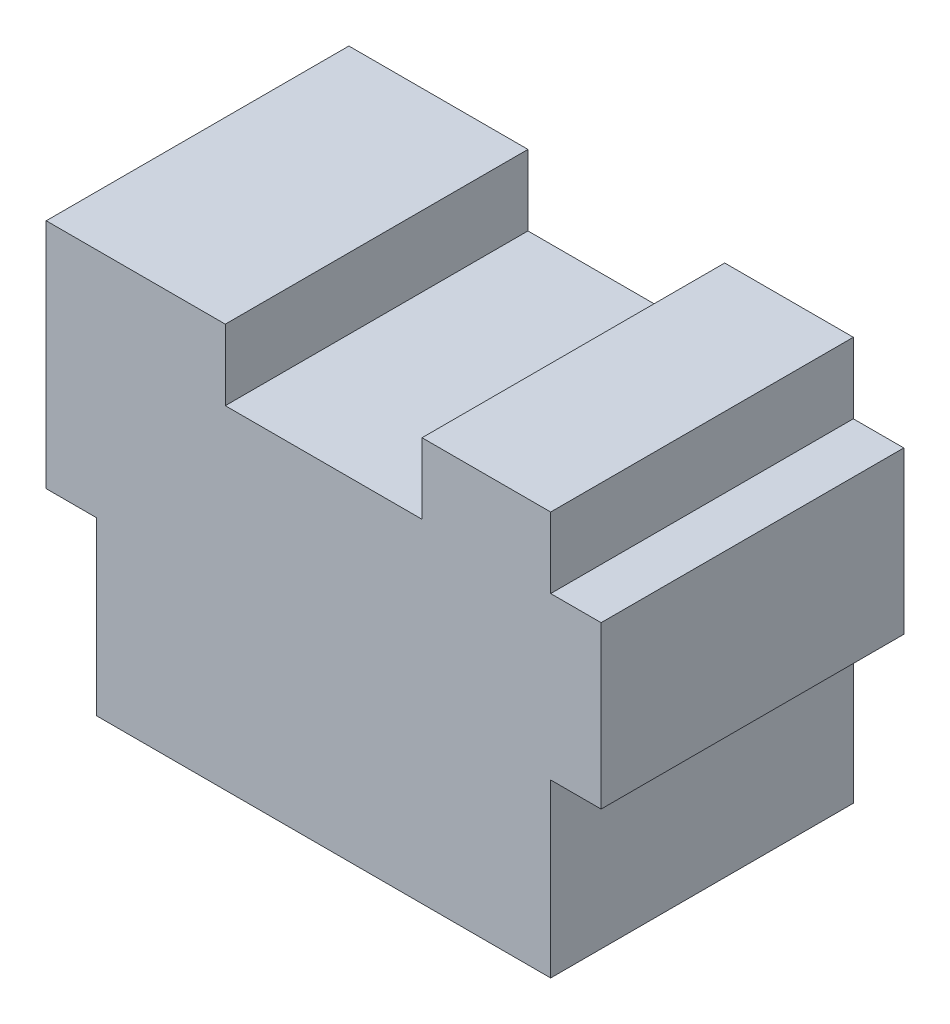
SolidWorks part; units mm, degrees
ref_plane "Спереди" through (0, 0, 0) normal (0, 0, 1) x (1, 0, 0)
ref_plane "Сверху" through (0, 0, 0) normal (0, 1, 0) x (1, 0, 0)
ref_plane "Справа" through (0, 0, 0) normal (1, 0, 0) x (0, 0, -1)
sketch "Эскиз1" plane through (0, 0, 0) normal (0, 0, 1) x (1, 0, 0)
  line L0 (0, 20) -> (0, -20) construction
  line L1 (-27.5, -20) -> (27.5, -20)
  line L2 (-27.5, -20) -> (-27.5, 20)
  line L3 (-27.5, 20) -> (27.5, 20)
  line L4 (27.5, -20) -> (27.5, 20)
  line L5 (-27.5, -20) -> (27.5, 20) construction
  line L6 (-27.5, 20) -> (27.5, -20) construction
  line L8 (9.75, 13) -> (-9.75, 13)
  line L9 (9.75, 13) -> (9.75, 20)
  line L10 (9.75, 20) -> (-9.75, 20)
  line L11 (-9.75, 13) -> (-9.75, 20)
  line L12 (9.75, 13) -> (-9.75, 20) construction
  line L13 (9.75, 20) -> (-9.75, 13) construction
  line L14 (27.5, 20) -> (22.5, 20)
  line L15 (27.5, 20) -> (27.5, 13)
  line L16 (27.5, 13) -> (22.5, 13)
  line L17 (22.5, 20) -> (22.5, 13)
  line L18 (27.5, -20) -> (22.5, -20)
  line L19 (27.5, -20) -> (27.5, -3)
  line L20 (27.5, -3) -> (22.5, -3)
  line L21 (22.5, -20) -> (22.5, -3)
  line L22 (-27.5, -20) -> (-22.5, -20)
  line L23 (-27.5, -20) -> (-27.5, -3)
  line L24 (-27.5, -3) -> (-22.5, -3)
  line L25 (-22.5, -20) -> (-22.5, -3)
  point P0 (0, 0)
  point P8 (0, 16.5)
  dimension "D1" = 55
  dimension "D2" = 40
  dimension "D3" = 19.5
  dimension "D4" = 7
  dimension "D5" = 5
  dimension "D6" = 16
extrude "Бобышка-Вытянуть1" add sketch "Эскиз1" along normal blind 30 contours L25 L1 L21 L20 L4 L16 L17 L3 L9 L8 L11 L2 L24
sketch "Эскиз2" plane through (0, 0, 0) normal (1, 0, 0) x (0, 0, -1)
  line L0 (0, -20) -> (0, -11)
  line L1 (0, -20) -> (0, -3) construction
  line L2 (0, -11) -> (-26, -20)
  line L4 (-30, -20) -> (0, -20) construction
  line L5 (-26, -20) -> (0, -20)
  dimension "D1" = 9
  dimension "D2" = 26
extrude "Вырез-Вытянуть1" cut sketch "Эскиз2" against normal up to surface and the other way up to surface up to face at (-9.75, 16.5, 15) other way up to face at (9.75, 16.5, 15)
